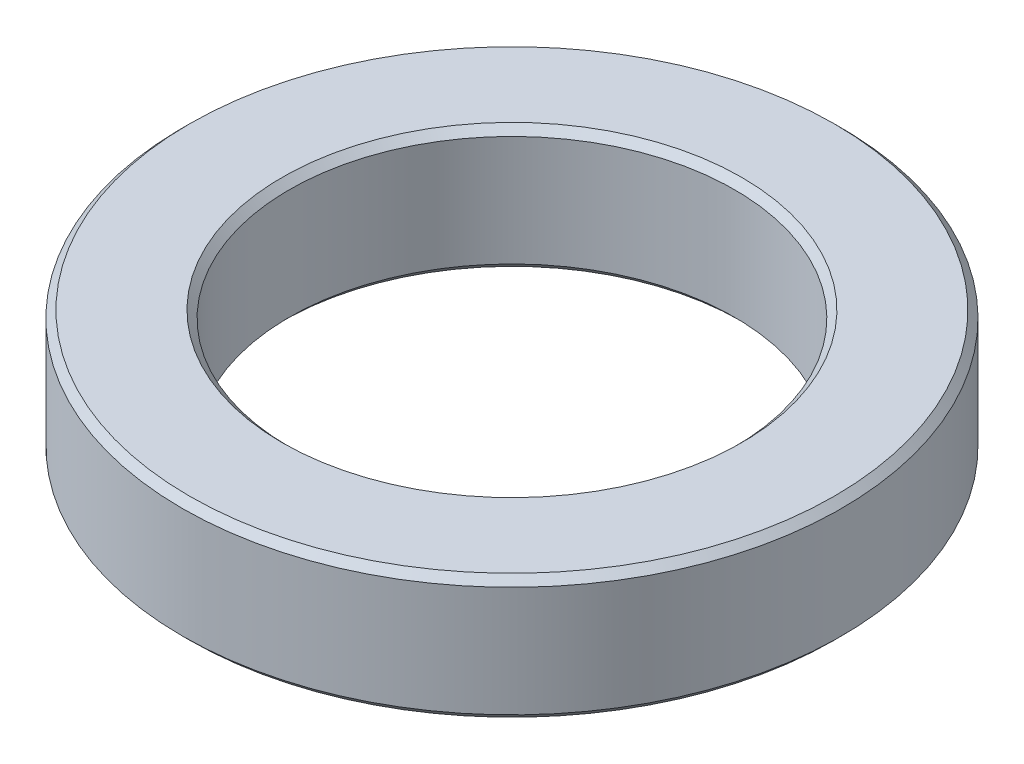
SolidWorks part; units mm, degrees
material "Chrome Stainless Steel - Modified"
ref_plane "Front Plane" through (0, 0, 0) normal (0, 0, 1) x (1, 0, 0)
ref_plane "Top Plane" through (0, 0, 0) normal (0, 1, 0) x (1, 0, 0)
ref_plane "Right Plane" through (0, 0, 0) normal (1, 0, 0) x (0, 0, -1)
sketch "Sketch1" plane through (0, 0, 0) normal (0, 1, 0) x (1, 0, 0)
  circle A0 centre (0, 0) radius 12.5
  circle A1 centre (0, 0) radius 18.5
  dimension "D1" = 25
  dimension "D2" = 37
extrude "Boss-Extrude1" add sketch "Sketch1" along normal blind 7
chamfer "Chamfer1" distance 0.4 angle 45 4 edges at (0, 0, 12.5) (0, 7, 12.5) (0, 0, 18.5) (0, 7, 18.5)
